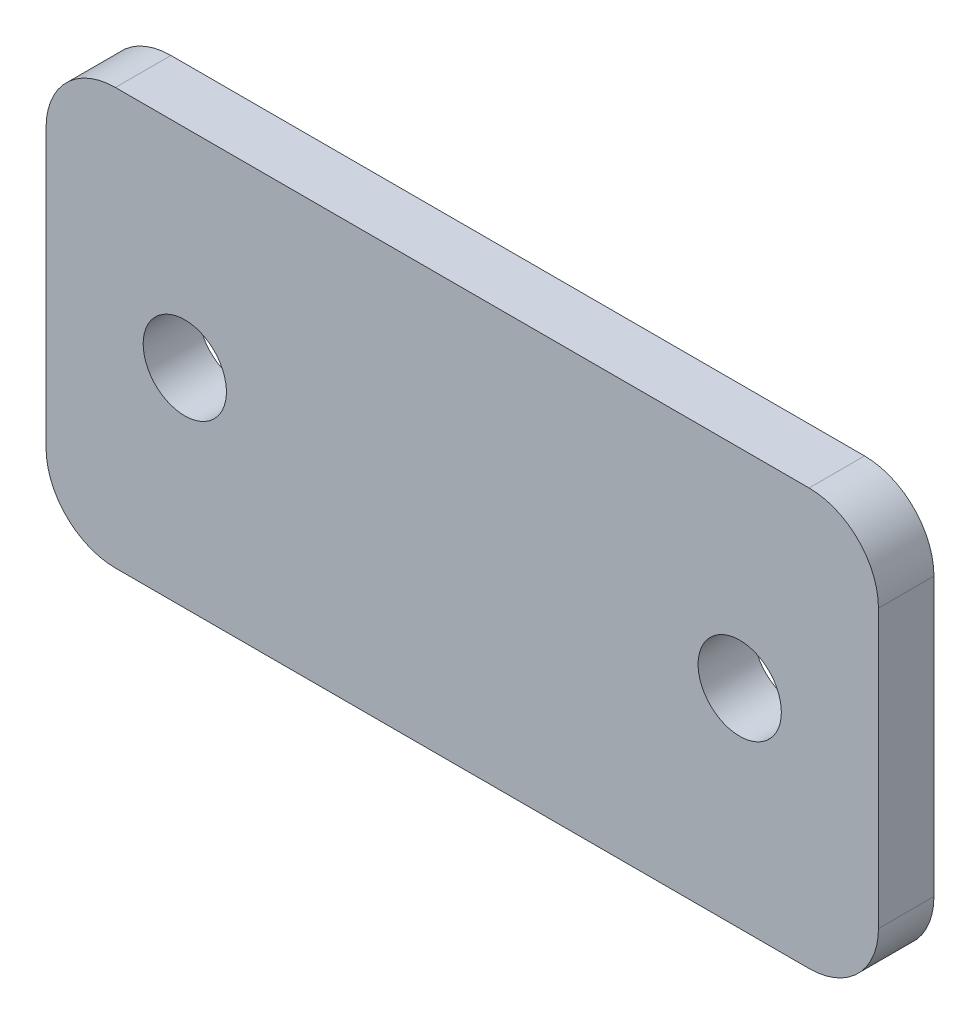
SolidWorks part; units mm, degrees
ref_plane "Front Plane" through (0, 0, 0) normal (0, 0, 1) x (1, 0, 0)
ref_plane "Top Plane" through (0, 0, 0) normal (0, 1, 0) x (1, 0, 0)
ref_plane "Right Plane" through (0, 0, 0) normal (1, 0, 0) x (0, 0, -1)
sketch "Model" plane through (0, 0, 0) normal (0, 0, 1) x (1, 0, 0)
  line L0 (0, 0) -> (0, 15) construction
  line L1 (-12.5, 15) -> (12.5, 15)
  line L2 (-15, 12.5) -> (-15, 2.5)
  line L3 (-12.5, 0) -> (12.5, 0)
  line L4 (15, 12.5) -> (15, 2.5)
  line L5 (-15, 7.5) -> (15, 7.5) construction
  arc A0 (-12.5, 15) -> (-15, 12.5) centre (-12.5, 12.5) ccw
  arc A1 (-15, 2.5) -> (-12.5, 0) centre (-12.5, 2.5) ccw
  arc A2 (12.5, 0) -> (15, 2.5) centre (12.5, 2.5) ccw
  arc A3 (15, 12.5) -> (12.5, 15) centre (12.5, 12.5) ccw
  circle A4 centre (10, 7.5) radius 1.5
  circle A5 centre (-10, 7.5) radius 1.5
  dimension "D1" = 5
  dimension "D4" = 3
  dimension "D5" = 15
  dimension "D2" = 15
  dimension "D3" = 20
extrude "Boss-Extrude1" add sketch "Model" along normal blind 2
equation "\"acrylic-thickness\" = 2mm"
equation "\"D1@Boss-Extrude1\" = \"acrylic-thickness\""
